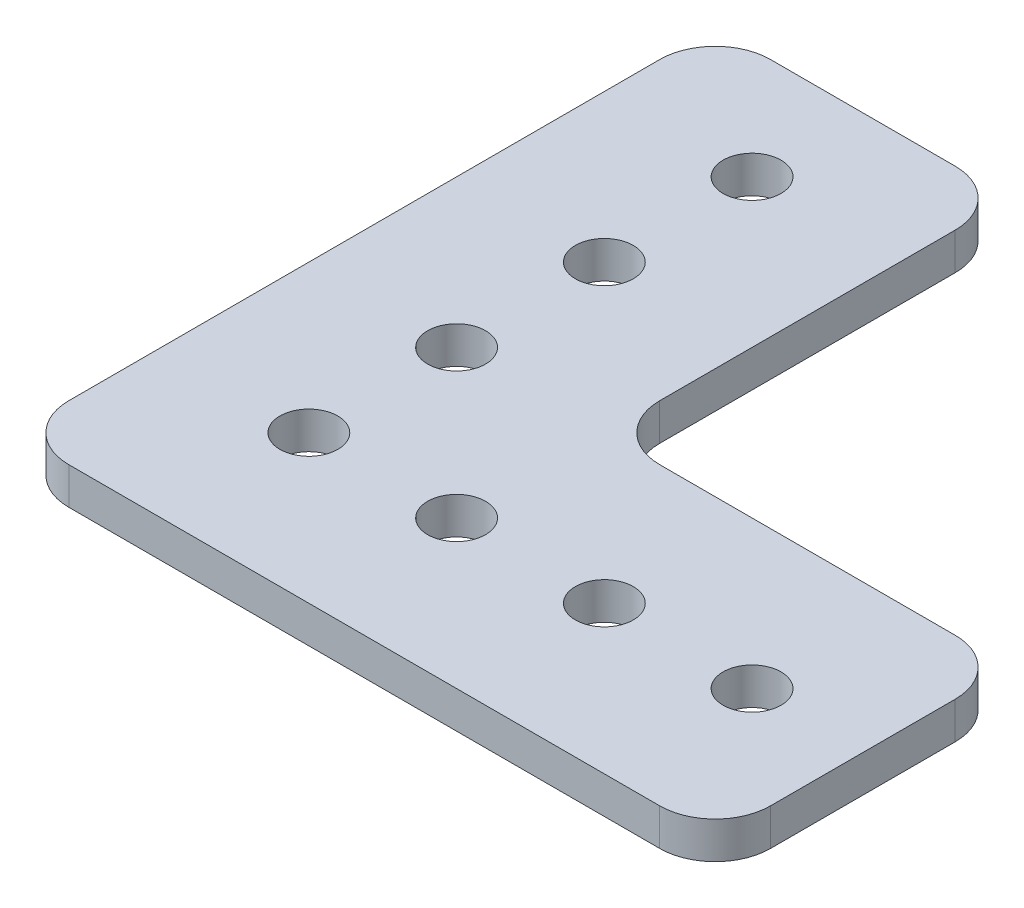
SolidWorks part; units mm, degrees
material "6061-T6 (SS)"
ref_plane "Front Plane" through (0, 0, 0) normal (0, 0, 1) x (1, 0, 0)
ref_plane "Top Plane" through (0, 0, 0) normal (0, 1, 0) x (1, 0, 0)
ref_plane "Right Plane" through (0, 0, 0) normal (1, 0, 0) x (0, 0, -1)
sketch "Sketch1" plane through (0, 0, 0) normal (0, 1, 0) x (1, 0, 0)
  line L0 (0, 0) -> (0, 60.325)
  line L1 (0, 60.325) -> (25.4, 60.325)
  line L2 (25.4, 60.325) -> (25.4, 25.4)
  line L3 (25.4, 25.4) -> (60.325, 25.4)
  line L4 (60.325, 25.4) -> (60.325, 0)
  line L5 (60.325, 0) -> (0, 0)
  circle A1 centre (12.7, 12.7) radius 2.4892
  circle A2 centre (12.7, 25.4) radius 2.4892
  circle A3 centre (12.7, 38.1) radius 2.4892
  circle A4 centre (25.4, 12.7) radius 2.4892
  circle A5 centre (38.1, 12.7) radius 2.4892
  circle A6 centre (50.8, 12.7) radius 2.4892
  circle A7 centre (12.7, 50.8) radius 2.4892
  dimension "D3" = 60.325
  dimension "D4" = 4.9784
  dimension "D5" = 12.7
  dimension "D6" = 12.7
  dimension "D8" = 12.7
  dimension "D10" = 12.7
  dimension "D1" = 25.4
  dimension "D2" = 25.4
  dimension "D7" = 4
  dimension "D9" = 4
extrude "Boss-Extrude1" add sketch "Sketch1" along normal blind 3.175
fillet "Fillet1" radius 4.7625 6 edges at (0, 1.5875, 0) (0, 1.5875, -60.325) (25.4, 1.5875, -25.4) (60.325, 1.5875, -25.4) (60.325, 1.5875, 0) (25.4, 1.5875, -60.325)
